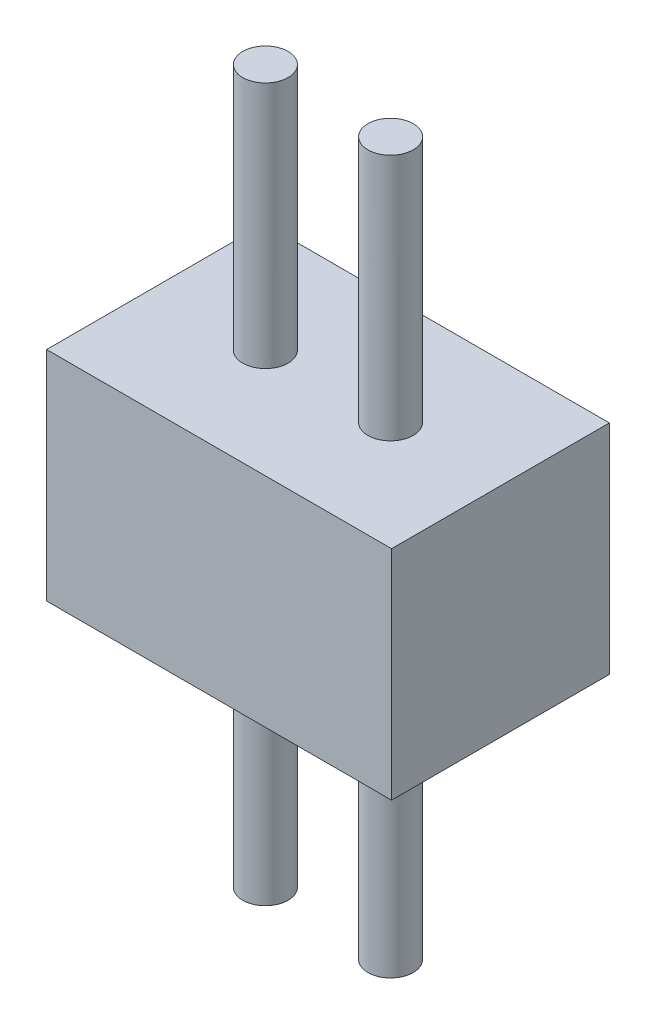
SolidWorks part; units mm, degrees
ref_plane "Front Plane" through (0, 0, 0) normal (0, 0, 1) x (1, 0, 0)
ref_plane "Top Plane" through (0, 0, 0) normal (0, 1, 0) x (1, 0, 0)
ref_plane "Right Plane" through (0, 0, 0) normal (1, 0, 0) x (0, 0, -1)
sketch "Sketch1" plane through (0, 0, 0) normal (0, 1, 0) x (1, 0, 0)
  line L1 (0, 0) -> (3.5, 0)
  line L2 (0, 0) -> (0, 2.21)
  line L3 (0, 2.21) -> (3.5, 2.21)
  line L4 (3.5, 0) -> (3.5, 2.21)
  dimension "D1" = 2.21
  dimension "D2" = 3.5
extrude "Boss-Extrude1" add sketch "Sketch1" along normal blind 2.21
sketch "Sketch2" plane through (0, 0, 0) normal (0, -1, 0) x (1, 0, 0)
  line L0 (1.75, 0) -> (1.75, -2.21) construction
  line L1 (0, 0) -> (3.5, 0) construction
  line L2 (3.5, -2.21) -> (0, -2.21) construction
  line L3 (0, -1.105) -> (3.5, -1.105) construction
  line L4 (0, -2.21) -> (0, 0) construction
  line L5 (3.5, 0) -> (3.5, -2.21) construction
  circle A0 centre (1.115, -1.105) radius 0.23
  circle A1 centre (2.385, -1.105) radius 0.23
  dimension "D2" = 0.46
  dimension "D1" = 1.27
  dimension "D3" = 0.635
extrude "Boss-Extrude2" add sketch "Sketch2" along normal blind 2.51
sketch "Sketch3" plane through (0, 2.21, 0) normal (0, 1, 0) x (1, 0, 0)
  circle A0 centre (2.385, 1.105) radius 0.23 construction
  circle A1 centre (1.115, 1.105) radius 0.23 construction
  circle A2 centre (2.385, 1.105) radius 0.23
  circle A3 centre (1.115, 1.105) radius 0.23
extrude "Boss-Extrude3" add sketch "Sketch3" along normal blind 2.51
equation "\"D3@Sketch2\"=\"D1@Sketch2\"/2"
